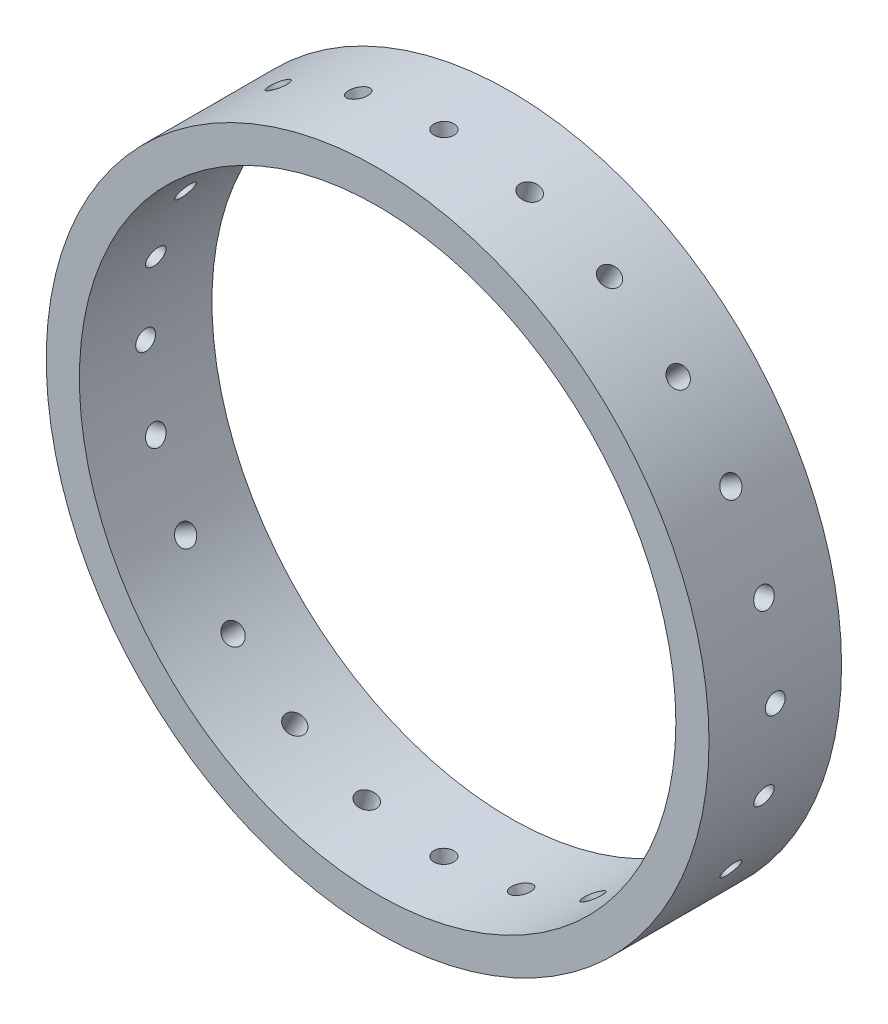
SolidWorks part; units mm, degrees
ref_plane "Front Plane" through (0, 0, 0) normal (0, 0, 1) x (1, 0, 0)
ref_plane "Top Plane" through (0, 0, 0) normal (0, 1, 0) x (1, 0, 0)
ref_plane "Right Plane" through (0, 0, 0) normal (1, 0, 0) x (0, 0, -1)
sketch "Sketch1" plane through (0, 0, 0) normal (0, 0, 1) x (1, 0, 0)
  circle A0 centre (0, 0) radius 50
  dimension "D1" = 100
extrude "Boss-Extrude1" add sketch "Sketch1" along normal mid plane 20
sketch "Sketch2" plane through (0, 0, 10) normal (0, 0, 1) x (1, 0, 0)
  circle A0 centre (0, 0) radius 45
  dimension "D1" = 90
extrude "Cut-Extrude1" cut sketch "Sketch2" against normal blind 20
sketch "Sketch3" plane through (0, 0, 0) normal (0, 0, 1) x (1, 0, 0)
  line L0 (0, 0) -> (0, 76.9935)
ref_plane "Plane1" through (0, 50, 0) normal (0, 1, 0) x (1, 0, 0)
sketch "Sketch4" plane through (0, 50, 0) normal (0, 1, 0) x (1, 0, 0)
  circle A0 centre (0, 0) radius 1.5
  dimension "D1" = 3
extrude "Cut-Extrude2" cut sketch "Sketch4" against normal blind 20
pattern_circular "CirPattern1" count 24 over 360 about axis through (0, 0, 10) along (0, 0, -1) of "Cut-Extrude2"
